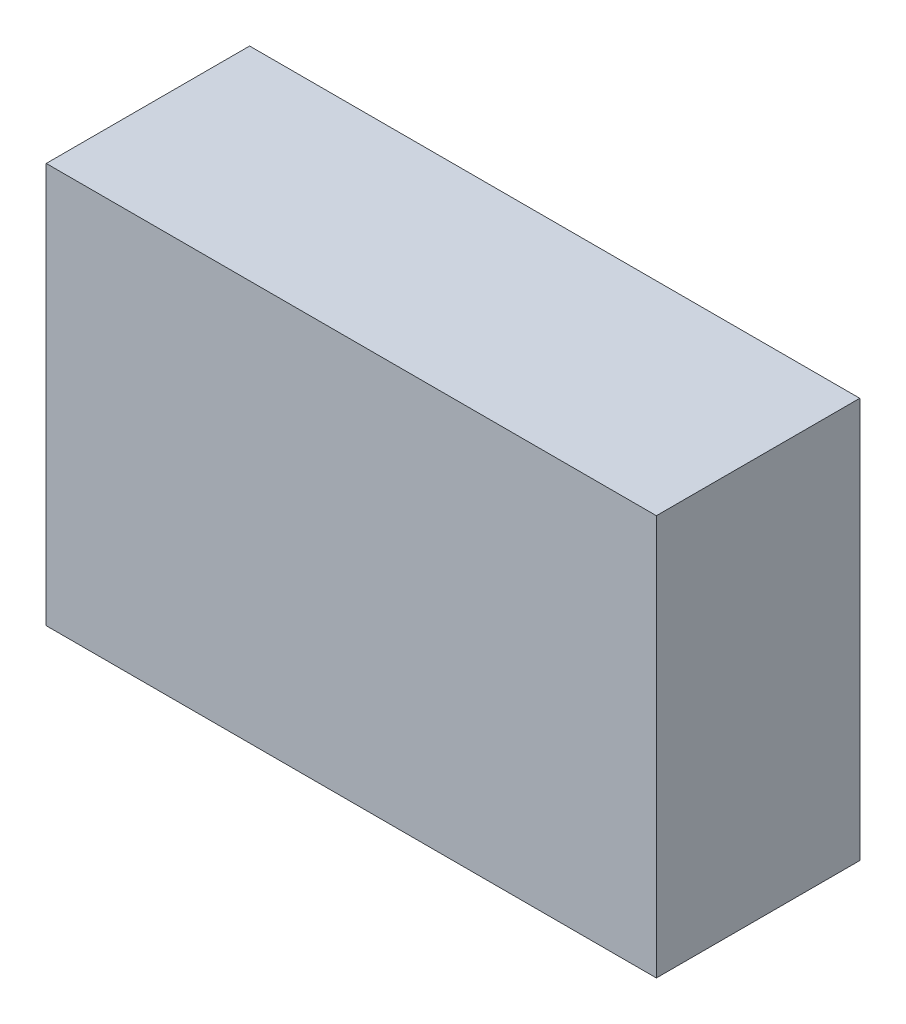
SolidWorks part; units mm, degrees
ref_plane "Front Plane" through (0, 0, 0) normal (0, 0, 1) x (1, 0, 0)
ref_plane "Top Plane" through (0, 0, 0) normal (0, 1, 0) x (1, 0, 0)
ref_plane "Right Plane" through (0, 0, 0) normal (1, 0, 0) x (0, 0, -1)
sketch "Sketch1" plane through (0, 0, 0) normal (0, 1, 0) x (1, 0, 0)
  line L1 (-3.81, -1.27) -> (3.81, -1.27)
  line L2 (-3.81, -1.27) -> (-3.81, 1.27)
  line L3 (-3.81, 1.27) -> (3.81, 1.27)
  line L4 (3.81, -1.27) -> (3.81, 1.27)
  line L5 (-3.81, -1.27) -> (3.81, 1.27) construction
  line L6 (-3.81, 1.27) -> (3.81, -1.27) construction
  point P0 (0, 0)
  dimension "D1" = 7.62
  dimension "D2" = 2.54
extrude "Boss-Extrude1" add sketch "Sketch1" along normal blind 5
